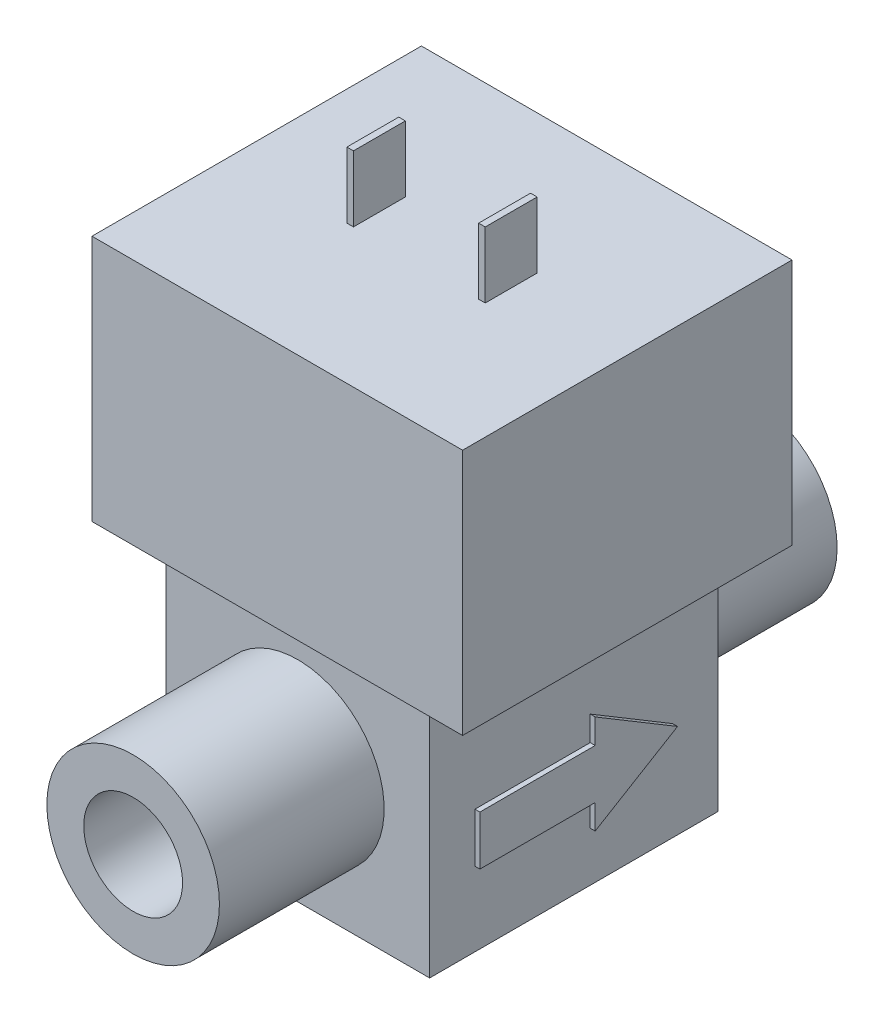
SolidWorks part; units mm, degrees
material "Brass"
ref_plane "Front Plane" through (0, 0, 0) normal (0, 0, 1) x (1, 0, 0)
ref_plane "Top Plane" through (0, 0, 0) normal (0, 1, 0) x (1, 0, 0)
ref_plane "Right Plane" through (0, 0, 0) normal (1, 0, 0) x (0, 0, -1)
other "Configuration Table"
sketch "Sketch1" plane through (0, 0, 0) normal (0, 1, 0) x (1, 0, 0)
  line L0 (-16, -17.5) -> (16, -17.5)
  line L1 (16, -17.5) -> (16, 17.5)
  line L2 (16, 17.5) -> (-16, 17.5)
  line L3 (-16, 17.5) -> (-16, -17.5)
extrude "Brass_Body" add sketch "Sketch1" along normal blind 30
sketch "Sketch2" plane through (0, 0, 0) normal (0, 1, 0) x (1, 0, 0)
  line L1 (-22.5, -20) -> (22.5, -20)
  line L2 (-22.5, -20) -> (-22.5, 20)
  line L3 (-22.5, 20) -> (22.5, 20)
  line L4 (22.5, -20) -> (22.5, 20)
  line L5 (-22.5, -20) -> (22.5, 20) construction
  line L6 (-22.5, 20) -> (22.5, -20) construction
  point P6 (0, 0)
  dimension "D1" = 45
  dimension "D2" = 40
extrude "Coil" add sketch "Sketch2" along normal blind 30 from offset 30
sketch "Sketch3" plane through (0, 0, 0) normal (0, 0, 1) x (1, 0, 0)
  circle A0 centre (0, 15) radius 10.4775
  dimension "D1" = 20.955
extrude "Inlet_Stub" add sketch "Sketch3" along normal blind 20 from offset 17.5
sketch "Sketch4" plane through (0, 0, 0) normal (0, 0, 1) x (1, 0, 0)
  circle A0 centre (0, 15) radius 10.4775
  dimension "D1" = 20.955
extrude "Outlet_Stub" add sketch "Sketch4" along normal blind 20 from offset 37.5
sketch "Sketch5" plane through (0, 0, 0) normal (0, 0, 1) x (1, 0, 0)
  circle A0 centre (0, 15) radius 6
  dimension "D1" = 12
extrude "Inlet_Bore" cut sketch "Sketch5" against normal blind 12 from offset 37.5
sketch "Sketch6" plane through (0, 0, 0) normal (0, 0, 1) x (1, 0, 0)
  circle A0 centre (0, 15) radius 6
  dimension "D1" = 12
extrude "Outlet_Bore" cut sketch "Sketch6" along normal blind 12 from offset 37.5
sketch "Sketch7" plane through (0, 0, 0) normal (0, 1, 0) x (1, 0, 0)
  line L0 (-8.4, -3.15) -> (-7.6, -3.15)
  line L1 (-7.6, -3.15) -> (-7.6, 3.15)
  line L2 (-7.6, 3.15) -> (-8.4, 3.15)
  line L3 (-8.4, 3.15) -> (-8.4, -3.15)
  line L4 (7.6, -3.15) -> (8.4, -3.15)
  line L5 (8.4, -3.15) -> (8.4, 3.15)
  line L6 (8.4, 3.15) -> (7.6, 3.15)
  line L7 (7.6, 3.15) -> (7.6, -3.15)
extrude "Spade_Terminals" add sketch "Sketch7" along normal blind 8 from offset 60
sketch "Sketch8" plane through (0, 0, 0) normal (1, 0, 0) x (0, 0, -1)
  line L0 (-12, 9) -> (2, 9)
  line L1 (2, 9) -> (2, 6)
  line L2 (2, 6) -> (12, 12)
  line L3 (12, 12) -> (2, 18)
  line L4 (2, 18) -> (2, 15)
  line L5 (2, 15) -> (-12, 15)
  line L6 (-12, 15) -> (-12, 9)
extrude "Flow_Arrow" add sketch "Sketch8" along normal blind 0.6 from offset 16
equation "\"Jar_OD\"= 90  'ASSUMED - Part G fallback - jar outer diameter"
equation "\"Jar_H\"= 120  'ASSUMED - Part G fallback - jar height"
equation "\"Pump_L\"= 45  'ASSUMED - Part G fallback"
equation "\"Pump_W\"= 24  'ASSUMED - Part G fallback"
equation "\"Pump_H\"= 33  'ASSUMED - Part G fallback"
equation "\"Pump_Outlet_OD\"= 7.5  'ASSUMED - Part G fallback"
equation "\"Tube_OD\"= 8  'ASSUMED - Part G fallback"
equation "\"Tube_ID\"= 6  'ASSUMED - Part G fallback"
equation "\"TDS_Body_Dia\"= 12  'ASSUMED - Part G fallback"
equation "\"TDS_Wet_Len\"= 45  'ASSUMED - Part G fallback - length in water"
equation "\"DS_Tube_Dia\"= 6  'ASSUMED - Part G fallback"
equation "\"DS_Tube_Len\"= 50  'ASSUMED - Part G fallback"
equation "\"ORP_Body_Dia\"= 12  'ASSUMED - Part G fallback"
equation "\"ORP_Body_Len\"= 150  'ASSUMED - Part G fallback"
equation "\"ORP_Cap_Dia\"= 16  'ASSUMED - Part G fallback"
equation "\"Turb_W\"= 33  'ASSUMED - Part G fallback - head width"
equation "\"Turb_D\"= 28  'ASSUMED - Part G fallback - head depth"
equation "\"Turb_H\"= 30  'ASSUMED - Part G fallback - head height"
equation "\"Turb_Slot_W\"= 10  'ASSUMED - Part G fallback - slot width"
equation "\"Flow_L\"= 62  'ASSUMED - Part G fallback YF-S201"
equation "\"Flow_W\"= 36  'ASSUMED - Part G fallback"
equation "\"Flow_H\"= 35  'ASSUMED - Part G fallback"
equation "\"Thread_G12_OD\"= 20.955  'ASSUMED - Part G fallback thread G1/2 (major diameter)"
equation "\"Valve_L\"= 75  'ASSUMED - Part G fallback"
equation "\"Valve_W\"= 45  'ASSUMED - Part G fallback"
equation "\"Valve_H\"= 60  'ASSUMED - Part G fallback"
equation "\"Tee_L\"= 40  'ASSUMED - Part G fallback - overall length"
equation "\"Tee_Branch_L\"= 25  'ASSUMED - Part G fallback"
equation "\"Tee_OD\"= 12  'ASSUMED - Part G fallback"
equation "\"Cuv_W\"= 12.5  'ASSUMED - old R3 cuvette (station suppressed in SS4)"
equation "\"Cuv_D\"= 12.5  'ASSUMED - old R3 cuvette (station suppressed in SS4)"
equation "\"Cuv_H\"= 45  'ASSUMED - old R3 cuvette (station suppressed in SS4)"
equation "\"LED_Board_L\"= 20  'ASSUMED - Part G fallback"
equation "\"LED_Board_W\"= 20  'ASSUMED - Part G fallback - LED at centre"
equation "\"GUVA_L\"= 20  'ASSUMED - Part G fallback"
equation "\"GUVA_W\"= 12  'ASSUMED - Part G fallback - sensor at centre"
equation "\"Reed_L\"= 27  'ASSUMED - Part G fallback MC-38 half"
equation "\"Reed_W\"= 14  'ASSUMED - Part G fallback"
equation "\"Reed_H\"= 8  'ASSUMED - Part G fallback"
equation "\"ESP_L\"= 51  'ASSUMED - Part G fallback"
equation "\"ESP_W\"= 28  'ASSUMED - Part G fallback"
equation "\"TFT_L\"= 58  'ASSUMED - Part G fallback - board"
equation "\"TFT_W\"= 35  'ASSUMED - Part G fallback - board"
equation "\"TFT_Win_L\"= 35  'ASSUMED - Part G fallback - visible window"
equation "\"TFT_Win_W\"= 28  'ASSUMED - Part G fallback - visible window"
equation "\"Relay_L\"= 50  'ASSUMED - Part G fallback"
equation "\"Relay_W\"= 26  'ASSUMED - Part G fallback"
equation "\"Relay_H\"= 19  'ASSUMED - Part G fallback"
equation "\"Mosfet_L\"= 34  'ASSUMED - Part G fallback"
equation "\"Mosfet_W\"= 17  'ASSUMED - Part G fallback"
equation "\"Mosfet_H\"= 12  'ASSUMED - Part G fallback"
equation "\"TDS_Board_L\"= 42  'ASSUMED - Part G fallback"
equation "\"TDS_Board_W\"= 32  'ASSUMED - Part G fallback"
equation "\"Turb_Board_L\"= 38  'ASSUMED - Part G fallback"
equation "\"Turb_Board_W\"= 28  'ASSUMED - Part G fallback"
equation "\"BNC_Thread_Dia\"= 9.5  'ASSUMED - Part G fallback"
equation "\"Plate_L\"= 420  'ASSUMED - Part G fallback"
equation "\"Plate_W\"= 297  'ASSUMED - Part G fallback"
equation "\"Plate_T\"= 6  'ASSUMED - Part G fallback"
equation "\"Probe_Clr\"= 0.3  'DESIGN VALUE - Part C rule 3 - printed probe hole = diameter + 0.3"
equation "\"Cuv_Clr\"= 0.2  'DESIGN VALUE - Part C rule 3 - cuvette pocket = size + 0.2"
equation "\"Label_H\"= 0.6  'DESIGN VALUE - Part D - raised label height"
equation "\"D1@Sketch2\" = \"Valve_W\""
equation "\"D1@Sketch3\" = \"Thread_G12_OD\""
equation "\"D1@Sketch4\" = \"Thread_G12_OD\""
equation "\"Booster_L\"= 150  'ASSUMED - Part G fallback - booster pump"
equation "\"Booster_W\"= 95  'ASSUMED - Part G fallback"
equation "\"Booster_H\"= 100  'ASSUMED - Part G fallback"
equation "\"PTube_OD\"= 6.35  'ASSUMED - Part G fallback - product tube 1/4 inch"
equation "\"Qz_Out\"= 12  'ASSUMED - Part G fallback - quartz channel outside square"
equation "\"Qz_Path\"= 10  'ASSUMED - Part G fallback - quartz channel inside light path"
equation "\"Qz_L\"= 40  'ASSUMED - Part G fallback - quartz channel length"
equation "\"LED860_Dia\"= 5  'ASSUMED - Part G fallback - 860 nm LED"
equation "\"BPW_L\"= 5.4  'ASSUMED - Part G fallback - BPW34"
equation "\"BPW_W\"= 4.3  'ASSUMED - Part G fallback - BPW34"
equation "\"Cart_Dia\"= 50  'ASSUMED - Part G fallback - sediment and pre-carbon cartridges"
equation "\"Cart_L\"= 255  'ASSUMED - Part G fallback"
equation "\"UF_Dia\"= 50  'ASSUMED - Part G fallback - UF cartridge"
equation "\"UF_L\"= 260  'ASSUMED - Part G fallback"
equation "\"RO_Dia\"= 62  'ASSUMED - Part G fallback - RO membrane housing"
equation "\"RO_L\"= 300  'ASSUMED - Part G fallback"
equation "\"UVC_Dia\"= 40  'ASSUMED - Part G fallback - UV-C chamber"
equation "\"UVC_L\"= 300  'ASSUMED - Part G fallback"
equation "\"Tank_W\"= 260  'ASSUMED - Part G fallback - storage tank"
equation "\"Tank_D\"= 160  'ASSUMED - Part G fallback"
equation "\"Tank_H\"= 300  'ASSUMED - Part G fallback"
equation "\"Cab_W\"= 400  'ASSUMED - Part G fallback - purifier cabinet"
equation "\"Cab_D\"= 270  'ASSUMED - Part G fallback"
equation "\"Cab_H\"= 560  'ASSUMED - Part G fallback"
equation "\"ORP_Board_L\"= 40  'ASSUMED - Part G fallback - ORP buffer board"
equation "\"ORP_Board_W\"= 30  'ASSUMED - Part G fallback"
equation "\"Opt_Board_L\"= 50  'ASSUMED - Part G fallback - optical front-end board"
equation "\"Opt_Board_W\"= 40  'ASSUMED - Part G fallback"
equation "\"Buck_L\"= 43  'ASSUMED - Part G fallback - 12 V to 5 V buck module"
equation "\"Buck_W\"= 21  'ASSUMED - Part G fallback"
equation "\"Buck_H\"= 14  'ASSUMED - Part G fallback"
equation "\"BB_L\"= 165  'ASSUMED - Part G fallback - breadboard (As_Built_R3 only)"
equation "\"BB_W\"= 55  'ASSUMED - Part G fallback"
equation "\"BB_H\"= 10  'ASSUMED - Part G fallback"
